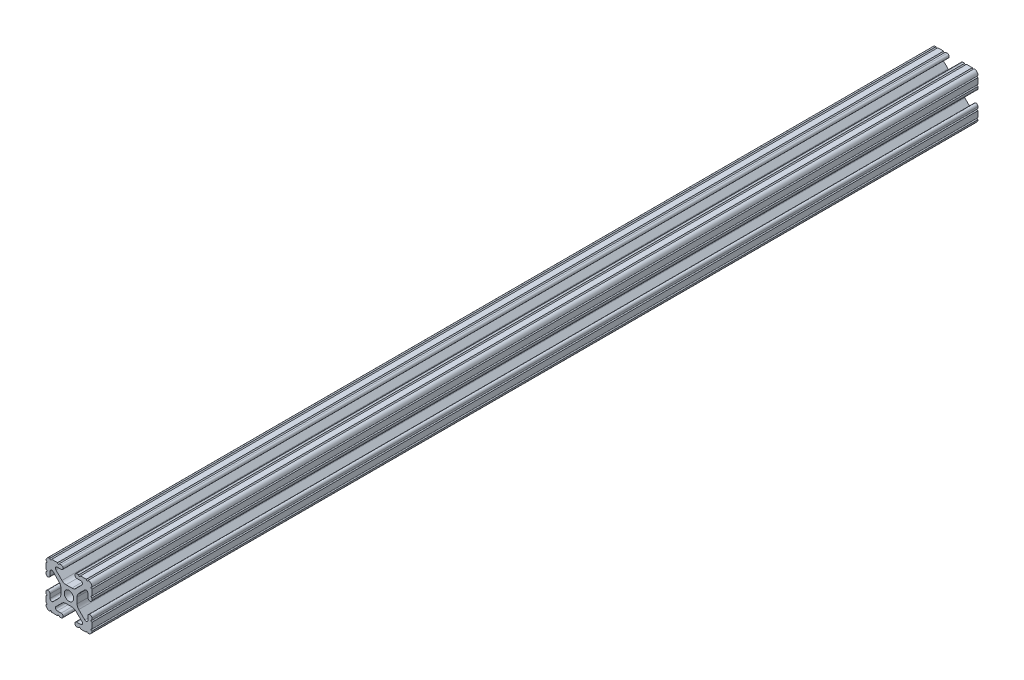
SolidWorks part; units mm, degrees
ref_plane "Front Plane" through (0, 0, 0) normal (0, 0, 1) x (1, 0, 0)
ref_plane "Top Plane" through (0, 0, 0) normal (0, 1, 0) x (1, 0, 0)
ref_plane "Right Plane" through (0, 0, 0) normal (1, 0, 0) x (0, 0, -1)
ref_plane "Plane1" through (0, 0, -25.4) normal (0, 0, -1) x (-1, 0, 0)
sketch "Sketch1" plane through (0, 0, -25.4) normal (0, 0, -1) x (-1, 0, 0)
  line L0 (12.7, -9.5504) -> (12.7, -6.3331)
  line L1 (12.7, -5.3171) -> (12.7, -4.3434)
  line L2 (10.4902, -4.3434) -> (10.4902, -6.4748)
  line L3 (8.7558, -7.1932) -> (5.4257, -3.8632)
  line L4 (4.4958, -1.6181) -> (4.4958, 1.6181)
  line L5 (5.4257, 3.8632) -> (8.7558, 7.1932)
  line L6 (10.4902, 6.4748) -> (10.4902, 4.3434)
  line L7 (12.7, 4.3434) -> (12.7, 5.3171)
  line L8 (12.7, 6.3331) -> (12.7, 9.5504)
  line L9 (9.5504, 12.7) -> (6.3331, 12.7)
  line L10 (5.3171, 12.7) -> (4.3434, 12.7)
  line L11 (4.3434, 10.4902) -> (6.4748, 10.4902)
  line L12 (7.1932, 8.7558) -> (3.8632, 5.4257)
  line L13 (1.6181, 4.4958) -> (-1.6181, 4.4958)
  line L14 (-3.8632, 5.4257) -> (-7.1932, 8.7558)
  line L15 (-6.4748, 10.4902) -> (-4.3434, 10.4902)
  line L16 (-4.3434, 12.7) -> (-5.3171, 12.7)
  line L17 (-6.3331, 12.7) -> (-9.5504, 12.7)
  line L18 (-12.7, 9.5504) -> (-12.7, 6.3331)
  line L19 (-12.7, 5.3171) -> (-12.7, 4.3434)
  line L20 (-10.4902, 4.3434) -> (-10.4902, 6.4748)
  line L21 (-8.7558, 7.1932) -> (-5.4257, 3.8632)
  line L22 (-4.4958, 1.6181) -> (-4.4958, -1.6181)
  line L23 (-5.4257, -3.8632) -> (-8.7558, -7.1932)
  line L24 (-10.4902, -6.4748) -> (-10.4902, -4.3434)
  line L25 (-12.7, -4.3434) -> (-12.7, -5.3171)
  line L26 (-12.7, -6.3331) -> (-12.7, -9.5504)
  line L27 (-9.5504, -12.7) -> (-6.3331, -12.7)
  line L28 (-5.3171, -12.7) -> (-4.3434, -12.7)
  line L29 (-4.3434, -10.4902) -> (-6.4748, -10.4902)
  line L30 (-7.1932, -8.7558) -> (-3.8632, -5.4257)
  line L31 (-1.6181, -4.4958) -> (1.6181, -4.4958)
  line L32 (3.8632, -5.4257) -> (7.1932, -8.7558)
  line L33 (6.4748, -10.4902) -> (4.3434, -10.4902)
  line L34 (4.3434, -12.7) -> (5.3171, -12.7)
  line L35 (6.3331, -12.7) -> (9.5504, -12.7)
  arc A0 (12.6998, -10.5664) -> (12.7, -9.5504) centre (12.7, -10.0584) cw
  arc A1 (12.7, -6.3331) -> (12.7, -5.3171) centre (12.7, -5.8251) cw
  arc A2 (12.7, -4.3434) -> (10.4902, -4.3434) centre (11.5951, -4.3434) ccw
  arc A3 (10.4902, -6.4748) -> (8.7558, -7.1932) centre (9.4742, -6.4748) cw
  arc A4 (5.4257, -3.8632) -> (4.4958, -1.6181) centre (7.6708, -1.6181) cw
  arc A5 (4.4958, 1.6181) -> (5.4257, 3.8632) centre (7.6708, 1.6181) cw
  arc A6 (8.7558, 7.1932) -> (10.4902, 6.4748) centre (9.4742, 6.4748) cw
  arc A7 (10.4902, 4.3434) -> (12.7, 4.3434) centre (11.5951, 4.3434) ccw
  arc A8 (12.7, 5.3171) -> (12.7, 6.3331) centre (12.7, 5.8251) cw
  arc A9 (12.7, 9.5504) -> (12.6998, 10.5664) centre (12.7, 10.0584) cw
  arc A10 (12.6998, 10.5664) -> (10.5664, 12.6998) centre (10.5918, 10.5918) ccw
  arc A11 (10.5664, 12.6998) -> (9.5504, 12.7) centre (10.0584, 12.7) cw
  arc A12 (6.3331, 12.7) -> (5.3171, 12.7) centre (5.8251, 12.7) cw
  arc A13 (4.3434, 12.7) -> (4.3434, 10.4902) centre (4.3434, 11.5951) ccw
  arc A14 (6.4748, 10.4902) -> (7.1932, 8.7558) centre (6.4748, 9.4742) cw
  arc A15 (3.8632, 5.4257) -> (1.6181, 4.4958) centre (1.6181, 7.6708) cw
  arc A16 (-1.6181, 4.4958) -> (-3.8632, 5.4257) centre (-1.6181, 7.6708) cw
  arc A17 (-7.1932, 8.7558) -> (-6.4748, 10.4902) centre (-6.4748, 9.4742) cw
  arc A18 (-4.3434, 10.4902) -> (-4.3434, 12.7) centre (-4.3434, 11.5951) ccw
  arc A19 (-5.3171, 12.7) -> (-6.3331, 12.7) centre (-5.8251, 12.7) cw
  arc A20 (-9.5504, 12.7) -> (-10.5664, 12.6998) centre (-10.0584, 12.7) cw
  arc A21 (-10.5664, 12.6998) -> (-12.6998, 10.5664) centre (-10.5918, 10.5918) ccw
  arc A22 (-12.6998, 10.5664) -> (-12.7, 9.5504) centre (-12.7, 10.0584) cw
  arc A23 (-12.7, 6.3331) -> (-12.7, 5.3171) centre (-12.7, 5.8251) cw
  arc A24 (-12.7, 4.3434) -> (-10.4902, 4.3434) centre (-11.5951, 4.3434) ccw
  arc A25 (-10.4902, 6.4748) -> (-8.7558, 7.1932) centre (-9.4742, 6.4748) cw
  arc A26 (-5.4257, 3.8632) -> (-4.4958, 1.6181) centre (-7.6708, 1.6181) cw
  arc A27 (-4.4958, -1.6181) -> (-5.4257, -3.8632) centre (-7.6708, -1.6181) cw
  arc A28 (-8.7558, -7.1932) -> (-10.4902, -6.4748) centre (-9.4742, -6.4748) cw
  arc A29 (-10.4902, -4.3434) -> (-12.7, -4.3434) centre (-11.5951, -4.3434) ccw
  arc A30 (-12.7, -5.3171) -> (-12.7, -6.3331) centre (-12.7, -5.8251) cw
  arc A31 (-12.7, -9.5504) -> (-12.6998, -10.5664) centre (-12.7, -10.0584) cw
  arc A32 (-12.6998, -10.5664) -> (-10.5664, -12.6998) centre (-10.5918, -10.5918) ccw
  arc A33 (-10.5664, -12.6998) -> (-9.5504, -12.7) centre (-10.0584, -12.7) cw
  arc A34 (-6.3331, -12.7) -> (-5.3171, -12.7) centre (-5.8251, -12.7) cw
  arc A35 (-4.3434, -12.7) -> (-4.3434, -10.4902) centre (-4.3434, -11.5951) ccw
  arc A36 (-6.4748, -10.4902) -> (-7.1932, -8.7558) centre (-6.4748, -9.4742) cw
  arc A37 (-3.8632, -5.4257) -> (-1.6181, -4.4958) centre (-1.6181, -7.6708) cw
  arc A38 (1.6181, -4.4958) -> (3.8632, -5.4257) centre (1.6181, -7.6708) cw
  arc A39 (7.1932, -8.7558) -> (6.4748, -10.4902) centre (6.4748, -9.4742) cw
  arc A40 (4.3434, -10.4902) -> (4.3434, -12.7) centre (4.3434, -11.5951) ccw
  arc A41 (5.3171, -12.7) -> (6.3331, -12.7) centre (5.8251, -12.7) cw
  arc A42 (9.5504, -12.7) -> (10.5664, -12.6998) centre (10.0584, -12.7) cw
  arc A43 (10.5664, -12.6998) -> (12.6998, -10.5664) centre (10.5918, -10.5918) ccw
  circle A44 centre (0, 0) radius 2.6035
extrude "Boss-Extrude1" add sketch "Sketch1" against normal blind 490.22
